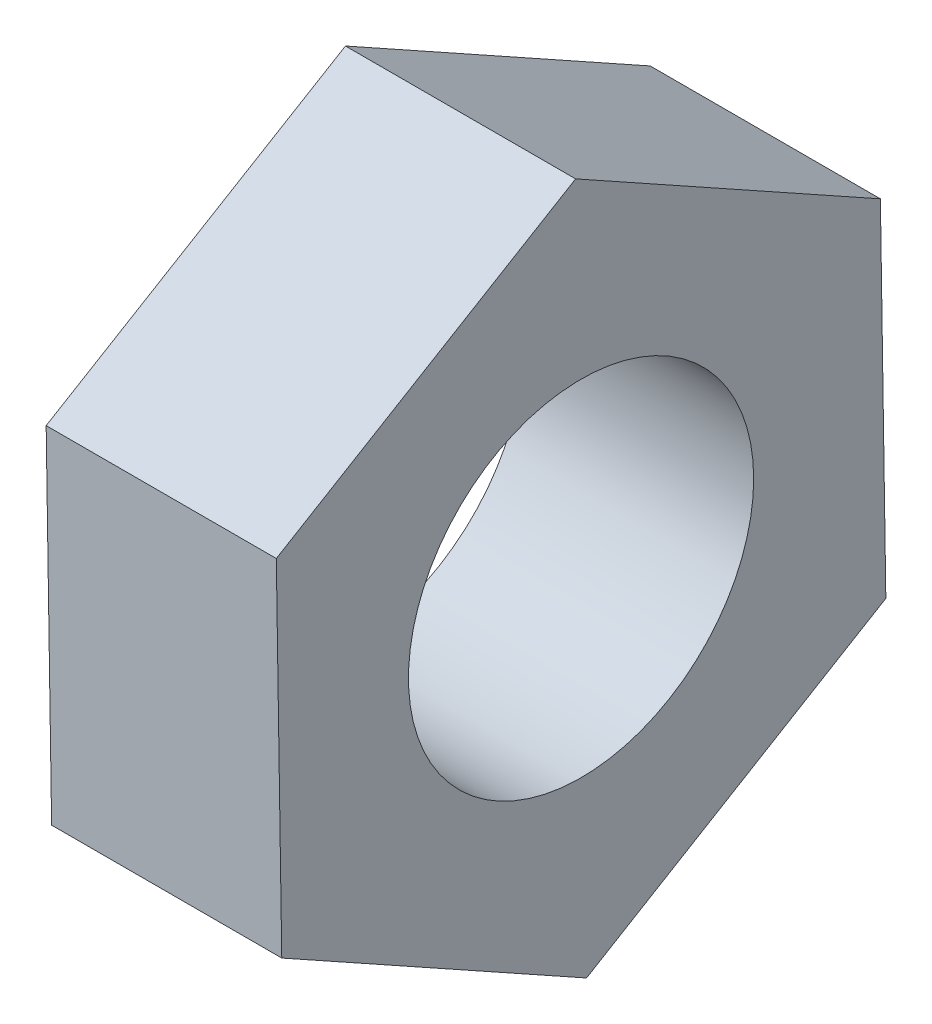
SolidWorks part; units mm, degrees
ref_plane "Front Plane" through (0, 0, 0) normal (0, 0, 1) x (1, 0, 0)
ref_plane "Top Plane" through (0, 0, 0) normal (0, 1, 0) x (1, 0, 0)
ref_plane "Right Plane" through (0, 0, 0) normal (1, 0, 0) x (0, 0, -1)
sketch "Sketch1" plane through (0, 0, 0) normal (1, 0, 0) x (0, 0, -1)
  line L1 (10.5936, -5.8971) -> (10.4038, 6.2258)
  line L2 (10.4038, 6.2258) -> (-0.1898, 12.1229)
  line L3 (-0.1898, 12.1229) -> (-10.5936, 5.8971)
  line L4 (-10.5936, 5.8971) -> (-10.4038, -6.2258)
  line L5 (-10.4038, -6.2258) -> (0.1898, -12.1229)
  line L6 (0.1898, -12.1229) -> (10.5936, -5.8971)
  circle A0 centre (0, 0) radius 10.5 construction
  circle A1 centre (0, 0) radius 6
  point P10 (0, 0)
  dimension "D1" = 21
  dimension "D2" = 12
extrude "Boss-Extrude1" add sketch "Sketch1" along normal blind 8
